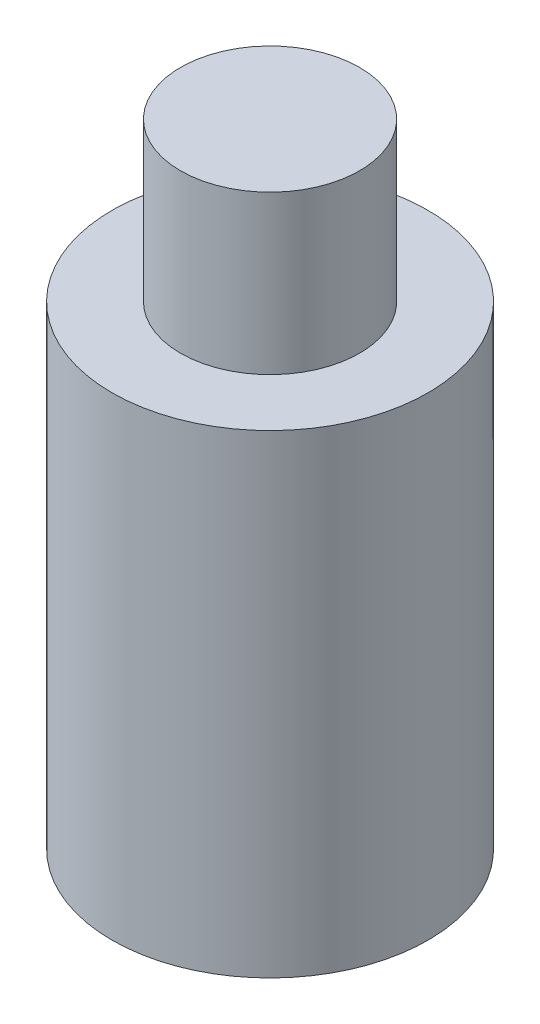
SolidWorks part; units mm, degrees
ref_plane "Front Plane" through (0, 0, 0) normal (0, 0, 1) x (1, 0, 0)
ref_plane "Top Plane" through (0, 0, 0) normal (0, 1, 0) x (1, 0, 0)
ref_plane "Right Plane" through (0, 0, 0) normal (1, 0, 0) x (0, 0, -1)
sketch "Sketch1" plane through (0, 3, 0) normal (0, 1, 0) x (1, 0, 0)
  circle A0 centre (21.5, 39) radius 3
  circle A1 centre (21.5, 39) radius 1.7
  dimension "D1" = 6
  dimension "D2" = 3.4
extrude "Boss-Extrude1" add sketch "Sketch1" along normal blind 9
sketch "Sketch2" plane through (0, 12, 0) normal (0, 1, 0) x (1, 0, 0)
  circle A0 centre (21.5, 39) radius 1.7
extrude "Boss-Extrude2" add sketch "Sketch2" along normal blind 3 separate body
